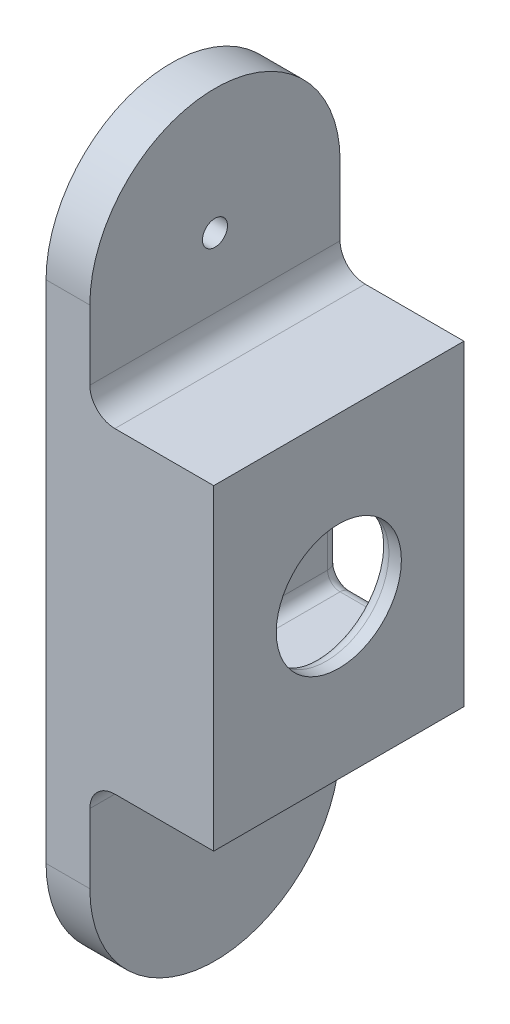
SolidWorks part; units mm, degrees
ref_plane "Front Plane" through (0, 0, 0) normal (0, 0, 1) x (1, 0, 0)
ref_plane "Top Plane" through (0, 0, 0) normal (0, 1, 0) x (1, 0, 0)
ref_plane "Right Plane" through (0, 0, 0) normal (1, 0, 0) x (0, 0, -1)
sketch "Sketch1" plane through (0, 0, 0) normal (1, 0, 0) x (0, 0, -1)
  line L0 (0, -20.2) -> (0, 20.2) construction
  line L1 (10, -10.2) -> (10, 10.2)
  line L2 (-10, 10.2) -> (-10, -10.2)
  line L3 (10, -20.2) -> (10, 20.2)
  line L4 (-10, 20.2) -> (-10, -20.2)
  circle A0 centre (0, 0) radius 5
  circle A1 centre (0, 20.2) radius 1
  circle A2 centre (0, -20.2) radius 1
  arc A3 (10, 20.2) -> (-10, 20.2) centre (0, 20.2) ccw
  arc A4 (-10, -20.2) -> (10, -20.2) centre (0, -20.2) ccw
  point P10 (0, 0)
extrude "Boss-Extrude1" add sketch "Sketch1" along normal blind 3.5
sketch "Sketch2" plane through (3.5, 0, 0) normal (1, 0, 0) x (0, 0, -1)
  line L0 (4.9941, 8.65) -> (-4.9941, 8.65) construction
  line L1 (9.815, 0) -> (4.9075, 8.5) construction
  line L2 (4.9075, 8.5) -> (-4.9075, 8.5) construction
  line L3 (-4.9075, 8.5) -> (-9.815, 0) construction
  line L4 (-9.815, 0) -> (-4.9075, -8.5) construction
  line L5 (-4.9075, -8.5) -> (4.9075, -8.5) construction
  line L6 (4.9075, -8.5) -> (9.815, 0) construction
  line L7 (-4.9941, 8.65) -> (-9.9882, 0)
  line L8 (-9.9882, 0) -> (-4.9941, -8.65)
  line L9 (-4.9941, -8.65) -> (4.9941, -8.65) construction
  line L10 (4.9941, -8.65) -> (9.9882, 0) construction
  line L11 (9.9882, 0) -> (4.9941, 8.65) construction
  line L12 (10, -20.2) -> (10, 20.2) construction
  line L13 (-10, -12.65) -> (10, -12.65)
  line L14 (-10, -12.65) -> (-10, 12.65)
  line L15 (-10, 12.65) -> (10, 12.65)
  line L16 (10, -12.65) -> (10, 12.65)
  line L17 (-10, -12.65) -> (10, 12.65) construction
  line L18 (-10, 12.65) -> (10, -12.65) construction
  line L20 (-4.9941, 8.65) -> (10, 8.65)
  line L21 (-4.9941, -8.65) -> (10, -8.65)
  circle A0 centre (0, 0) radius 5
  circle A1 centre (0, 0) radius 8.5 construction
  point P22 (-14.2732, 9.1629)
  point P25 (0, 8.65)
  point P28 (0, -8.65)
  line M21 (-10, 20.2) -> (-10, -20.2)
  line M23 (10, -20.2) -> (10, 20.2)
  dimension "D1" = 10
  dimension "D2" = 17
  dimension "D4" = 4
  dimension "D3" = 0.15
extrude "Boss-Extrude2" add sketch "Sketch2" along normal blind 7.9 contours L21 L8 L7 L20 L16 L15 L13 M21 M23
sketch "Sketch3" plane through (11.4, 0, 0) normal (1, 0, 0) x (0, 0, -1)
  line L1 (10, 12.65) -> (-10, 12.65)
  line L2 (10, 12.65) -> (10, -12.65)
  line L3 (10, -12.65) -> (-10, -12.65)
  line L4 (-10, 12.65) -> (-10, -12.65)
  circle A0 centre (0, 0) radius 5 construction
  circle A1 centre (0, 0) radius 5
extrude "Boss-Extrude3" add sketch "Sketch3" along normal blind 2
fillet "Fillet1" radius 2 3 edges at (7.45, 0, 9.9882) (3.5, 12.65, 0) (3.5, -12.65, 0)
fillet "Fillet2" radius 1 16 edges at (7.45, -8.65, -10) (7.45, 8.65, -10) (11.4, -8.65, -2.503) (11.4, 0, -10) (11.4, 8.65, -2.503) (11.4, 4.825, 7.2024) (11.4, 0, 9.6788) (11.4, -4.825, 7.2024) (11.4, 0, -5) (3.5, 8.65, -2.503) (3.5, 0, -10) (3.5, -8.65, -2.503) (3.5, -4.825, 7.2024) (3.5, 0, 9.6788) (3.5, 4.825, 7.2024) (3.5, 0, -5)
